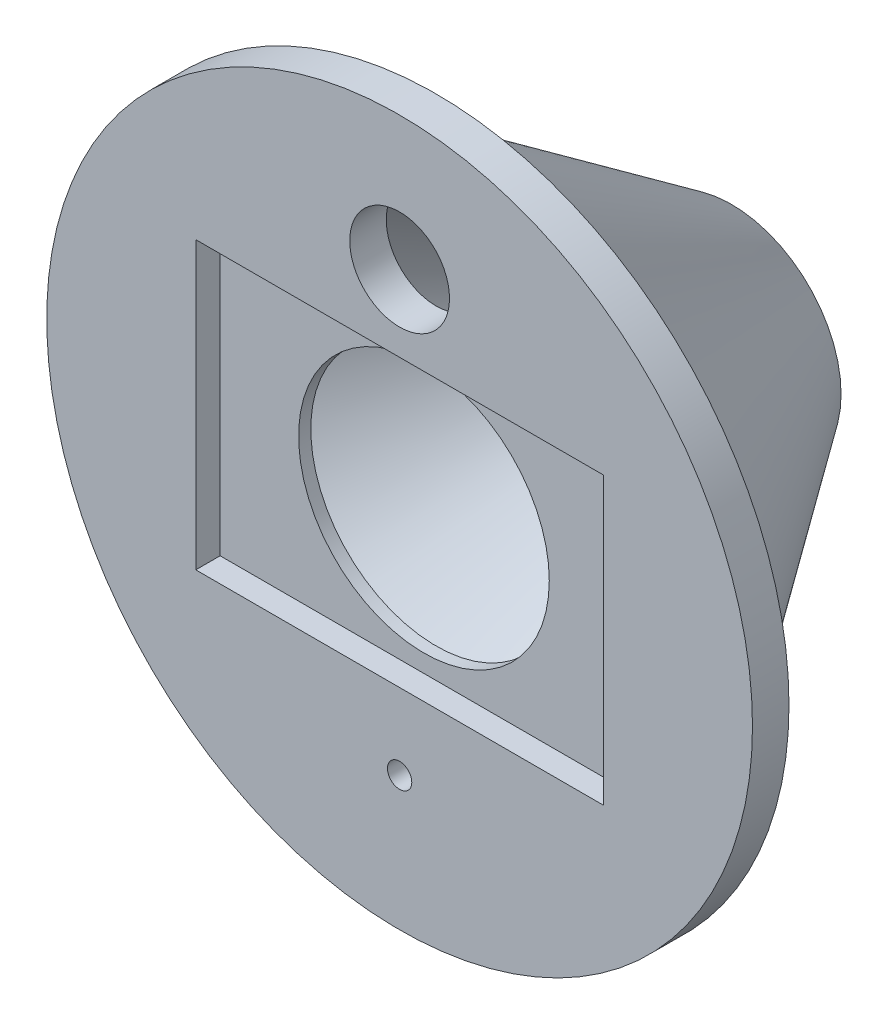
SolidWorks part; units mm, degrees
ref_plane "Front Plane" through (0, 0, 0) normal (0, 0, 1) x (1, 0, 0)
ref_plane "Top Plane" through (0, 0, 0) normal (0, 1, 0) x (1, 0, 0)
ref_plane "Right Plane" through (0, 0, 0) normal (1, 0, 0) x (0, 0, -1)
sketch "Sketch1" plane through (0, 0, 0) normal (0, 0, 1) x (1, 0, 0)
  circle A0 centre (0, 0) radius 9
extrude "Seal_cone" add sketch "Sketch1" along normal blind 24.2785 draft 35 draft outward yes
sketch "Sketch2" plane through (0, 0, 0) normal (0, 0, 1) x (1, 0, 0)
  circle A0 centre (0, 0) radius 7
extrude "Cone_hollow" cut sketch "Sketch2" along normal blind 24.2785 draft 35 draft outward yes
ref_plane "Plane_Z+24.28" through (0, 0, 24.2785) normal (0, 0, 1) x (1, 0, 0)
sketch "Sketch3" plane through (0, 0, 24.2785) normal (0, 0, 1) x (1, 0, 0)
  circle A0 centre (0, 0) radius 29
extrude "Top_plate" add sketch "Sketch3" along normal blind 3
ref_plane "Plane_Z+26.53" through (0, 0, 26.5285) normal (0, 0, 1) x (1, 0, 0)
sketch "Sketch4" plane through (0, 0, 26.5285) normal (0, 0, 1) x (1, 0, 0)
  line L0 (-16.75, -11.75) -> (16.75, -11.75)
  line L1 (16.75, -11.75) -> (16.75, 11.75)
  line L2 (16.75, 11.75) -> (-16.75, 11.75)
  line L3 (-16.75, 11.75) -> (-16.75, -11.75)
extrude "MQ3_pcb_pocket" cut sketch "Sketch4" against normal mid plane 2.5
ref_plane "Plane_Z+25.88" through (0, 0, 25.8785) normal (0, 0, 1) x (1, 0, 0)
sketch "Sketch5" plane through (0, 0, 25.8785) normal (0, 0, 1) x (1, 0, 0)
  circle A0 centre (0, 0) radius 10.3
  circle A1 centre (0, 18) radius 4.1
  circle A2 centre (0, -18) radius 1
  dimension "Mq3CanHole" = 20.6
  dimension "HoseHole" = 8.2
extrude "Can_hose_vent_holes" cut sketch "Sketch5" against normal mid plane 3.8
